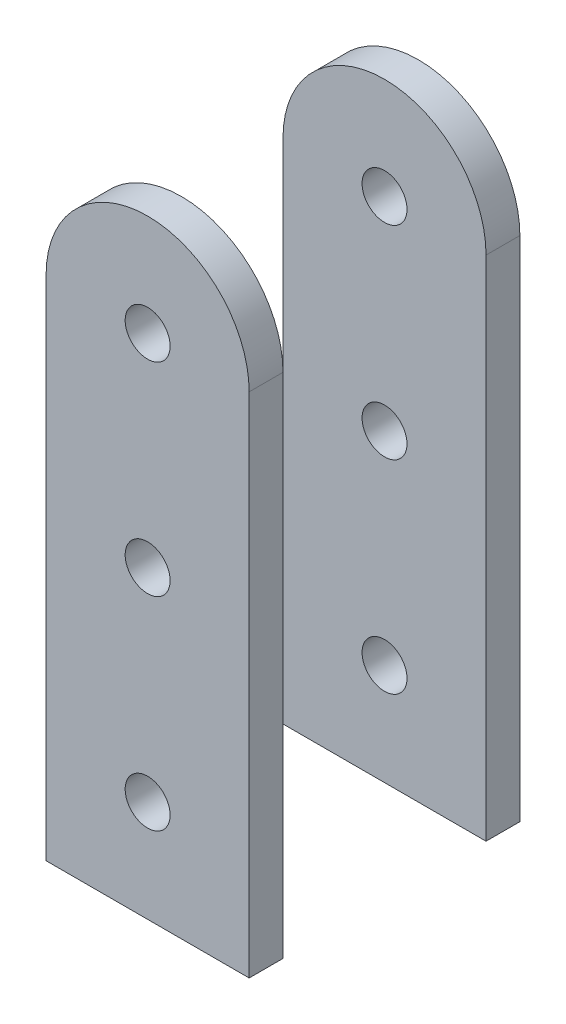
SolidWorks part; units mm, degrees
ref_plane "Front Plane" through (0, 0, 0) normal (0, 0, 1) x (1, 0, 0)
ref_plane "Top Plane" through (0, 0, 0) normal (0, 1, 0) x (1, 0, 0)
ref_plane "Right Plane" through (0, 0, 0) normal (1, 0, 0) x (0, 0, -1)
sketch "Sketch1" plane through (0, 0, 0) normal (0, 0, 1) x (1, 0, 0)
  line L0 (0, 47.625) -> (0, -47.625) construction
  line L2 (19.05, 47.625) -> (19.05, -47.625)
  line L3 (19.05, -47.625) -> (-19.05, -47.625)
  line L4 (-19.05, 47.625) -> (-19.05, -47.625)
  line L5 (19.05, 47.625) -> (-19.05, -47.625) construction
  line L6 (19.05, -47.625) -> (-19.05, 47.625) construction
  arc A0 (-19.05, 47.625) -> (19.05, 47.625) centre (0, 47.625) cw
  circle A1 centre (0, 47.625) radius 4.2164
  circle A2 centre (0, 9.525) radius 4.2164
  circle A3 centre (0, -28.575) radius 4.2164
  point P0 (0, 0)
  dimension "D2" = 8.4328
  dimension "D3" = 19.05
  dimension "D1" = 95.25
  dimension "D4" = 57.15
extrude "Boss-Extrude1" add sketch "Sketch1" against normal blind 50.8
sketch "Sketch2" plane through (19.05, 0, 0) normal (1, 0, 0) x (0, 0, -1)
  line L0 (6.35, -47.625) -> (6.35, 66.675)
  line L1 (50.8, -47.625) -> (0, -47.625) construction
  line L2 (50.8, 66.675) -> (0, 66.675) construction
  line L3 (6.35, 66.675) -> (44.45, 66.675)
  line L4 (44.45, 66.675) -> (44.45, -47.625)
  line L5 (44.45, -47.625) -> (6.35, -47.625)
  line L6 (0, -47.625) -> (0, 47.625) construction
  line L7 (50.8, -47.625) -> (50.8, 47.625) construction
  dimension "D1" = 6.35
  dimension "D2" = 6.35
extrude "Cut-Extrude1" cut sketch "Sketch2" against normal blind 50.8
